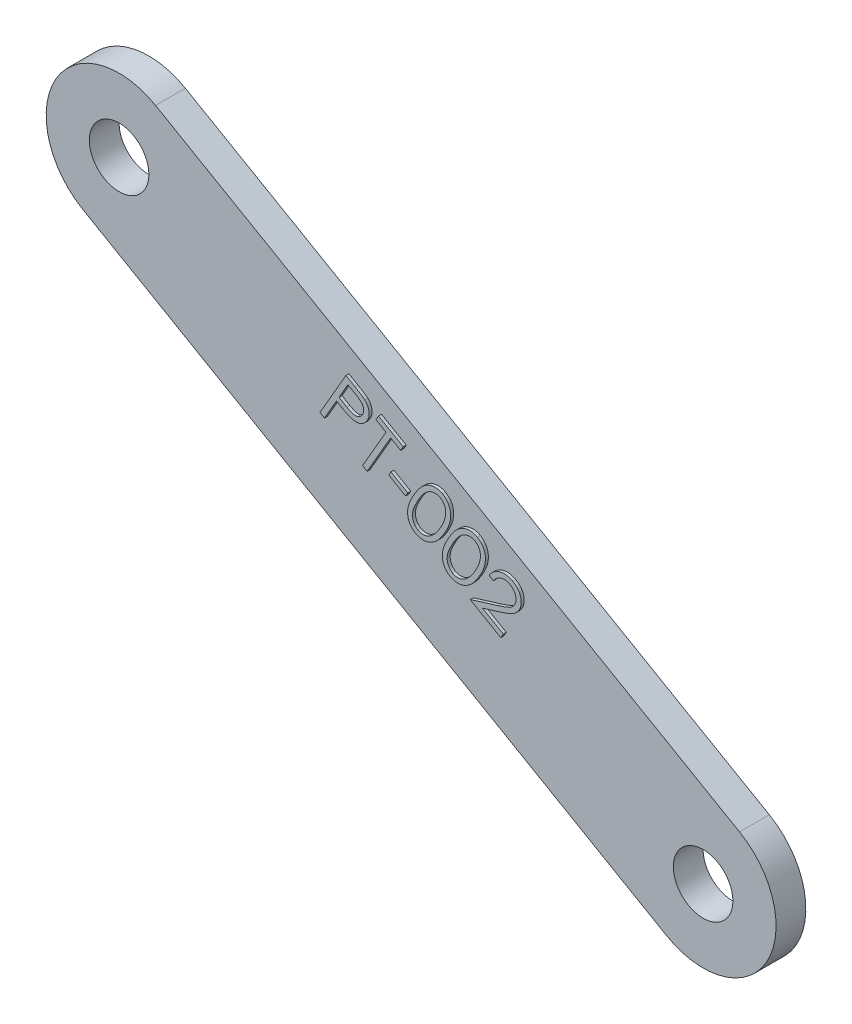
SolidWorks part; units mm, degrees
ref_plane "Piano frontale" through (0, 0, 0) normal (0, 0, 1) x (1, 0, 0)
ref_plane "Piano superiore" through (0, 0, 0) normal (0, 1, 0) x (1, 0, 0)
ref_plane "Piano destro" through (0, 0, 0) normal (1, 0, 0) x (0, 0, -1)
sketch "Schizzo1" plane through (0, 0, 0) normal (0, 0, 1) x (1, 0, 0)
  line L0 (0, 0) -> (0, 55.2) construction
  line L1 (0, 55.2) -> (0, 45.3)
  line L2 (0, 0) -> (39.231, 22.65) construction
  line L3 (0, 45.3) -> (39.231, 22.65) construction
  line L4 (0, 0) -> (39.231, 22.65) construction
  line L5 (-2.45, 4.2435) -> (36.781, 26.8935)
  line L6 (2.45, -4.2435) -> (41.681, 18.4065)
  line L7 (0, 45.3) -> (39.231, 22.65) construction
  line L8 (2.45, 49.5435) -> (41.681, 26.8935)
  line L9 (-2.45, 41.0565) -> (36.781, 18.4065)
  circle A0 centre (0, 0) radius 2.9
  circle A1 centre (39.231, 22.65) radius 2
  arc A2 (-2.45, 4.2435) -> (2.45, -4.2435) centre (0, 0) ccw
  arc A3 (41.681, 18.4065) -> (36.781, 26.8935) centre (39.231, 22.65) ccw
  circle A4 centre (0, 45.3) radius 2
  arc A5 (2.45, 49.5435) -> (-2.45, 41.0565) centre (0, 45.3) ccw
  arc A6 (36.781, 18.4065) -> (41.681, 26.8935) centre (39.231, 22.65) ccw
  point P7 (19.6155, 11.325)
  point P13 (19.6155, 33.975)
extrude "Estrusione-Estrusione1" add sketch "Schizzo1" along normal blind 2
sketch "Schizzo2" plane through (0, 0, 2) normal (0, 0, 1) x (1, 0, 0)
  line L0 (0, 45.3) -> (39.231, 22.65) construction
  text T0 "PT-002\r\n"
extrude "Estrusione-Estrusione2" add sketch "Schizzo2" along normal blind 0.2
